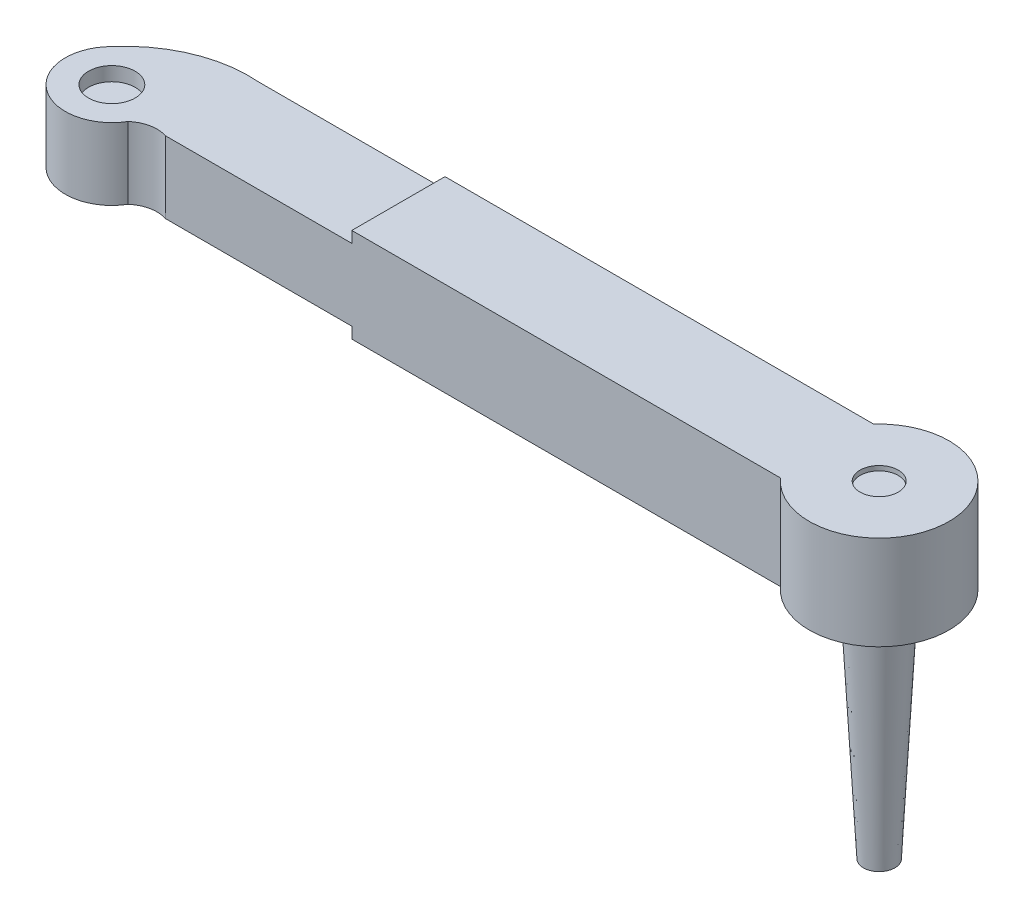
SolidWorks part; units mm, degrees
ref_plane "Alzado" through (0, 0, 0) normal (0, 0, 1) x (1, 0, 0)
ref_plane "Planta" through (0, 0, 0) normal (0, 1, 0) x (1, 0, 0)
ref_plane "Vista lateral" through (0, 0, 0) normal (1, 0, 0) x (0, 0, -1)
sketch "Croquis1" plane through (0, 0, 0) normal (0, 1, 0) x (1, 0, 0)
  line L1 (-33, -5) -> (33, -5)
  line L2 (-33, -5) -> (-33, 5)
  line L3 (-33, 5) -> (33, 5)
  line L5 (-33, -5) -> (33, 5) construction
  line L6 (-33, 5) -> (33, -5) construction
  arc A0 (33, 5) -> (33, -5) centre (38.5902, 0) cw
  point P0 (0, 0)
  dimension "D3" = 7.5
  dimension "D1" = 66
  dimension "D2" = 10
extrude "Saliente-Extruir1" add sketch "Croquis1" along normal blind 10.1
sketch "Croquis2" plane through (0, 10.1, 0) normal (0, 1, 0) x (1, 0, 0)
  circle A0 centre (38.5902, 0) radius 2.05
  dimension "D1" = 4.1
extrude "Cortar-Extruir1" cut sketch "Croquis2" against normal blind 0.5
sketch "Croquis3" plane through (0, 0, 5) normal (0, 0, 1) x (1, 0, 0)
  line L1 (-33, 10.1) -> (-13, 10.1)
  line L2 (-33, 10.1) -> (-33, 8.9)
  line L3 (-33, 8.9) -> (-13, 8.9)
  line L4 (-13, 10.1) -> (-13, 8.9)
  dimension "D1" = 1.2
  dimension "D2" = 20
extrude "Cortar-Extruir2" cut sketch "Croquis3" against normal through all
ref_plane "Plano1" through (0, 5.05, 0) normal (0, 1, 0) x (1, 0, 0)
mirror "Simetría1" about plane through (0, 5.05, 0) normal (0, 1, 0) of "Cortar-Extruir2"
sketch "Croquis6" plane through (0, 8.9, 0) normal (0, 1, 0) x (1, 0, 0)
  line L0 (-33, 5) -> (-33, -5) construction
  line L1 (-33, 5) -> (-33, -5)
  arc A0 (-33, 0) -> (-40.6248, -3.1216) centre (-34.0711, -8.2568) ccw construction
  arc A1 (-33, 5) -> (-44.1484, 0.4229) centre (-34.0711, -8.2568) ccw
  arc A2 (-33, -5) -> (-36.3301, -5.6779) centre (-34.0711, -8.2568) ccw
  arc A4 (-44.1484, 0.4229) -> (-36.3301, -5.6779) centre (-40.6248, -3.1216) ccw
  point P3 (-36.055, -0.979)
  point P10 (0, 0)
  point P11 (-33, -4.9681)
  point P13 (0, 0)
  point P15 (-34.2117, -5.3712)
  point P16 (-43.7649, 0)
  point P17 (-42.0096, 1.8104)
  point P18 (-42.6427, 1.5229)
  point P19 (-43.7359, 0)
  point P20 (-44.1484, 0.4229)
  dimension "D1" = 13.3
  dimension "D2" = 4.9979
extrude "Saliente-Extruir3" add sketch "Croquis6" against normal up to vertex
sketch "Croquis7" plane through (0, 8.9, 0) normal (0, 1, 0) x (1, 0, 0)
  circle A0 centre (-40.6248, -3.1216) radius 2.5
  dimension "D1" = 5
extrude "Cortar-Extruir4" cut sketch "Croquis7" against normal blind 1.5
mirror "Simetría3" about plane through (0, 5.05, 0) normal (0, 1, 0) of "Cortar-Extruir4"
sketch "Croquis8" plane through (0, 0, 0) normal (0, -1, 0) x (1, 0, 0)
  circle A0 centre (38.5902, 0) radius 3
  dimension "D1" = 6
extrude "Saliente-Extruir4" add sketch "Croquis8" along normal blind 25 draft 3
